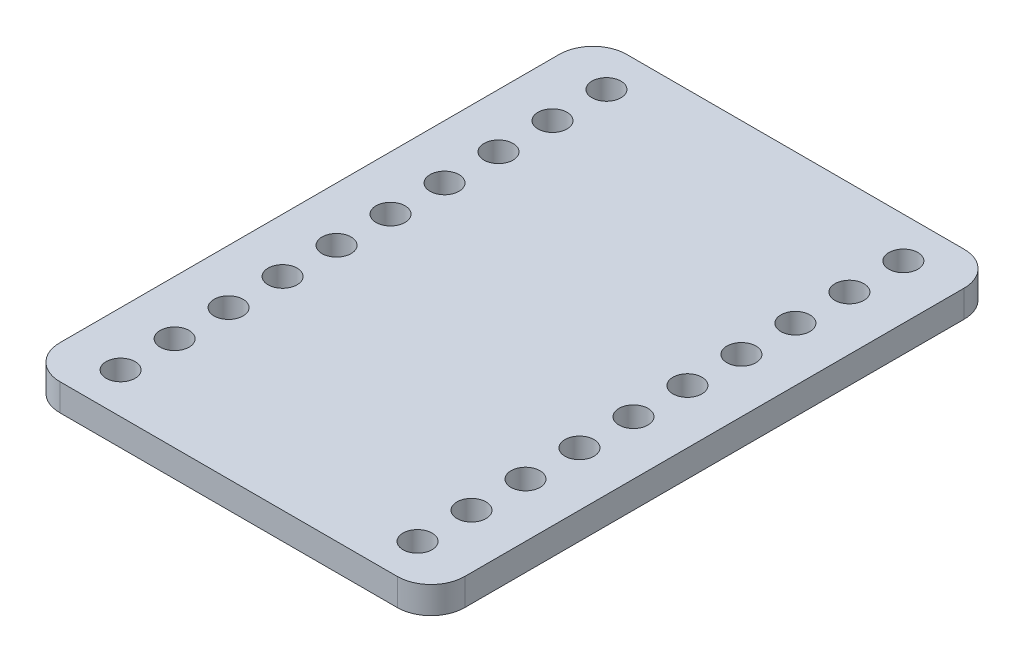
SolidWorks part; units mm, degrees
ref_plane "Front Plane" through (0, 0, 0) normal (0, 0, 1) x (1, 0, 0)
ref_plane "Top Plane" through (0, 0, 0) normal (0, 1, 0) x (1, 0, 0)
ref_plane "Right Plane" through (0, 0, 0) normal (1, 0, 0) x (0, 0, -1)
sketch "Sketch2" plane through (0, 0, 0) normal (0, 1, 0) x (1, 0, 0)
  line L0 (-30, 0) -> (30, 0) construction
  line L1 (-30, 42) -> (30, 42)
  line L2 (-30, 42) -> (-30, -42)
  line L3 (-30, -42) -> (30, -42)
  line L4 (30, 42) -> (30, -42)
  line L5 (-30, 42) -> (30, -42) construction
  line L6 (-30, -42) -> (30, 42) construction
  line L7 (-30, 36) -> (30, 36) construction
  line L8 (-22, 36) -> (22, 36) construction
  line L9 (-22, 36) -> (-22, 28) construction
  circle A0 centre (-22, 36) radius 2.15
  circle A1 centre (22, 36) radius 2.15
  circle A2 centre (22, 28) radius 2.15
  circle A3 centre (22, 20) radius 2.15
  circle A4 centre (22, 12) radius 2.15
  circle A5 centre (22, 4) radius 2.15
  circle A6 centre (22, -4) radius 2.15
  circle A7 centre (22, -12) radius 2.15
  circle A8 centre (22, -20) radius 2.15
  circle A9 centre (22, -28) radius 2.15
  circle A10 centre (22, -36) radius 2.15
  circle A11 centre (-22, 28) radius 2.15
  circle A12 centre (-22, 20) radius 2.15
  circle A13 centre (-22, 12) radius 2.15
  circle A14 centre (-22, 4) radius 2.15
  circle A15 centre (-22, -4) radius 2.15
  circle A16 centre (-22, -12) radius 2.15
  circle A17 centre (-22, -20) radius 2.15
  circle A18 centre (-22, -28) radius 2.15
  circle A19 centre (-22, -36) radius 2.15
  point P0 (0, 0)
  dimension "D4" = 4.3
  dimension "D1" = 84
  dimension "D2" = 60
  dimension "D3" = 6
  dimension "D5" = 8
  dimension "D8" = 90
  dimension "D9" = 44
  dimension "D6" = 2
  dimension "D7" = 10
extrude "Boss-Extrude2" add sketch "Sketch2" along normal blind 4
fillet "Fillet2" radius 5 4 edges at (30, 2, -42) (-30, 2, 42) (-30, 2, -42) (30, 2, 42)
